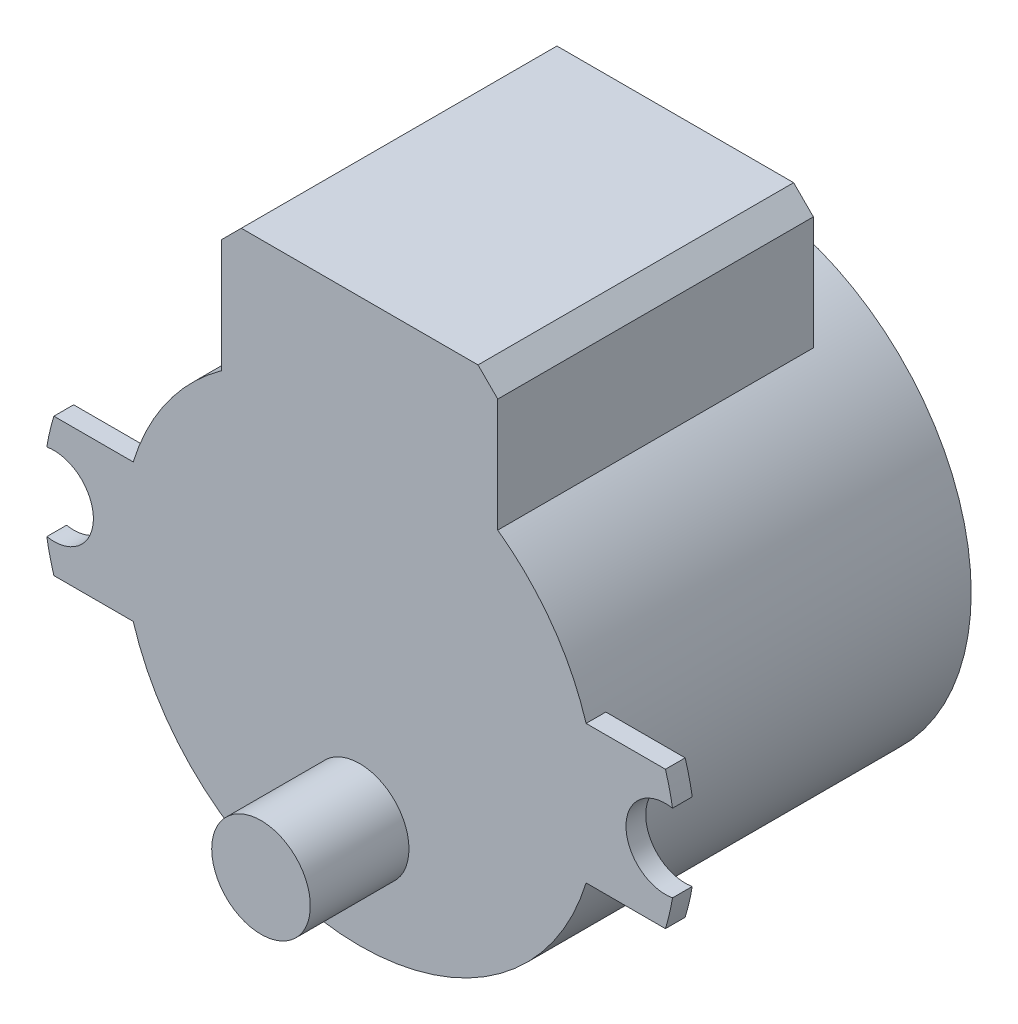
SolidWorks part; units mm, degrees
ref_plane "前视基准面" through (0, 0, 0) normal (0, 0, 1) x (1, 0, 0)
ref_plane "上视基准面" through (0, 0, 0) normal (0, 1, 0) x (1, 0, 0)
ref_plane "右视基准面" through (0, 0, 0) normal (1, 0, 0) x (0, 0, -1)
ref_plane "基准面1" through (0, 0, 0) normal (0, -1, 0) x (1, 0, 0)
sketch "草图1" plane through (0, 0, 0) normal (0, -1, 0) x (1, 0, 0)
  line L0 (12, 1) -> (0, 1)
  line L1 (0, 1) -> (0, -18)
  line L2 (0, -18) -> (12, -18)
  line L3 (12, -18) -> (12, 1)
  line L4 (0, 1) -> (0, -18) construction
  dimension "D1" = 12
  dimension "D2" = 19
revolve "旋转1" add sketch "草图1" angle 360 about L4
ref_plane "基准面2" through (0, 16.5, 0) normal (0, 1, 0) x (1, 0, 0)
sketch "草图2" plane through (0, 16.5, 0) normal (0, 1, 0) x (1, 0, 0)
  line L0 (-7, -1) -> (7, -1)
  line L1 (7, -1) -> (7, 15)
  line L2 (7, 15) -> (-7, 15)
  line L3 (-7, 15) -> (-7, -1)
  dimension "D1" = 14
  dimension "D2" = 16
extrude "凸台-拉伸1" add sketch "草图2" against normal up to next
ref_plane "基准面3" through (-3, 0, 0) normal (1, 0, 0) x (0, 0, -1)
sketch "草图3" plane through (-3, 0, 0) normal (1, 0, 0) x (0, 0, -1)
  line L0 (-1, 3.5) -> (0, 3.5)
  line L1 (0, 3.5) -> (0, -3.5)
  line L2 (0, -3.5) -> (-1, -3.5)
  line L3 (-1, -3.5) -> (-1, 3.5)
  dimension "D1" = 1
  dimension "D2" = 7
extrude "凸台-拉伸2" add sketch "草图3" along normal blind 4.0218 from surface starting at face at (0, 4.8734, -7)
ref_plane "基准面4" through (3, 0, 0) normal (-1, 0, 0) x (0, 0, 1)
sketch "草图4" plane through (3, 0, 0) normal (-1, 0, 0) x (0, 0, 1)
  line L0 (1, 3.5) -> (1, -3.5)
  line L1 (1, -3.5) -> (0, -3.5)
  line L2 (0, -3.5) -> (0, 3.5)
  line L3 (0, 3.5) -> (1, 3.5)
  dimension "D1" = 1
  dimension "D2" = 7
extrude "凸台-拉伸3" add sketch "草图4" along normal blind 4.0218 from surface starting at face at (4.7147, 3.5916, -3.25)
ref_plane "基准面5" through (0, -6.5, 0) normal (0, -1, 0) x (1, 0, 0)
sketch "草图5" plane through (0, -6.5, 0) normal (0, -1, 0) x (1, 0, 0)
  line L0 (2.5, 6) -> (0, 6)
  line L1 (0, 6) -> (0, 1)
  line L2 (0, 1) -> (2.5, 1)
  line L3 (2.5, 1) -> (2.5, 6)
  line L4 (0, 6) -> (0, 1) construction
  dimension "D1" = 2.5
  dimension "D2" = 5
revolve "旋转2" add sketch "草图5" angle 360 about L4
hole_wizard "Ø4.0 (4) 直径孔1" positions "草图7" profile "草图6" hole size "Ø4.0" standard "ANSI Metric"
sketch "草图7" plane through (0, 0, 1) normal (0, 0, 1) x (1, 0, 0)
  point P0 (-15.5, 0)
  point P1 (15.5, 0)
sketch "草图6" plane through (-15.5, 0, 1) normal (1, 0, 0) x (0, -1, 0)
  line L0 (0, 0) -> (0, 19)
  line L1 (0, 19) -> (2, 19)
  line L2 (2, 19) -> (2, 0)
  line L5 (2, 0) -> (0, 0)
  line L11 (0, -6.35) -> (0, 107.95) construction
  dimension "通孔孔直径" = 4
  dimension "通孔孔深度" = 19
chamfer "倒角1" distance 1 angle 45 2 edges at (7, 16.5, -7) (-7, 16.5, -7)
